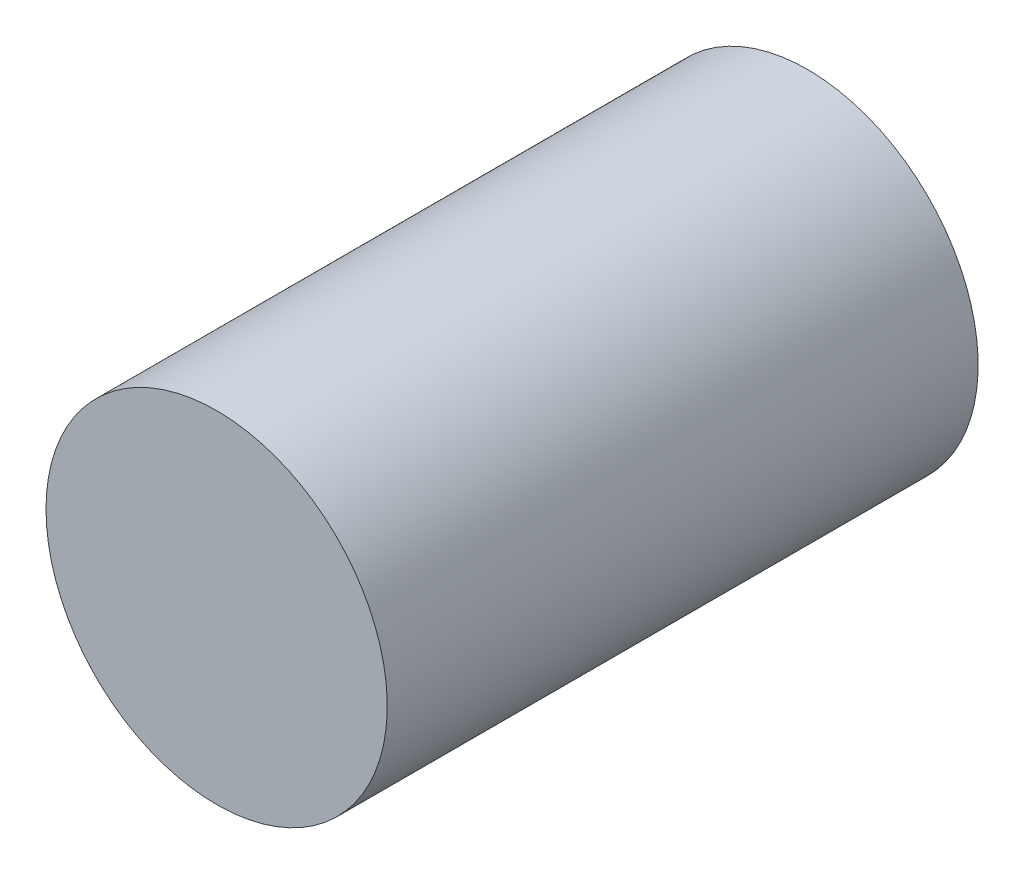
SolidWorks part; units mm, degrees
ref_plane "Front Plane" through (0, 0, 0) normal (0, 0, 1) x (1, 0, 0)
ref_plane "Top Plane" through (0, 0, 0) normal (0, 1, 0) x (1, 0, 0)
ref_plane "Right Plane" through (0, 0, 0) normal (1, 0, 0) x (0, 0, -1)
sketch "Sketch1" plane through (0, 0, 0) normal (0, 0, 1) x (1, 0, 0)
  circle A0 centre (0, 0) radius 17.325
  dimension "D1" = 34.65
extrude "Boss-Extrude1" add sketch "Sketch1" along normal blind 60
